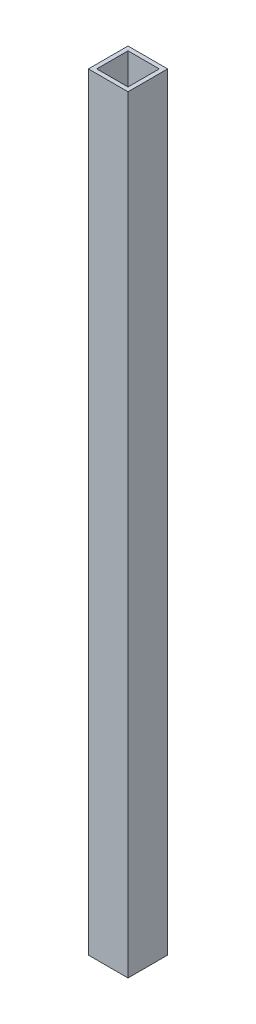
SolidWorks part; units mm, degrees
ref_plane "Front Plane" through (0, 0, 0) normal (0, 0, 1) x (1, 0, 0)
ref_plane "Top Plane" through (0, 0, 0) normal (0, 1, 0) x (1, 0, 0)
ref_plane "Right Plane" through (0, 0, 0) normal (1, 0, 0) x (0, 0, -1)
sketch "Sketch1" plane through (0, 0, 0) normal (0, 1, 0) x (1, 0, 0)
  line L1 (-9.5, -9.5) -> (9.5, -9.5)
  line L2 (-9.5, -9.5) -> (-9.5, 9.5)
  line L3 (-9.5, 9.5) -> (9.5, 9.5)
  line L4 (9.5, -9.5) -> (9.5, 9.5)
  line L5 (-9.5, -9.5) -> (9.5, 9.5) construction
  line L6 (-9.5, 9.5) -> (9.5, -9.5) construction
  point P0 (0, 0)
  dimension "D1" = 19
  dimension "D2" = 19
extrude "Extrude-Thin1" add sketch "Sketch1" along normal blind 368 thin thin type one direction reverse wall 2
